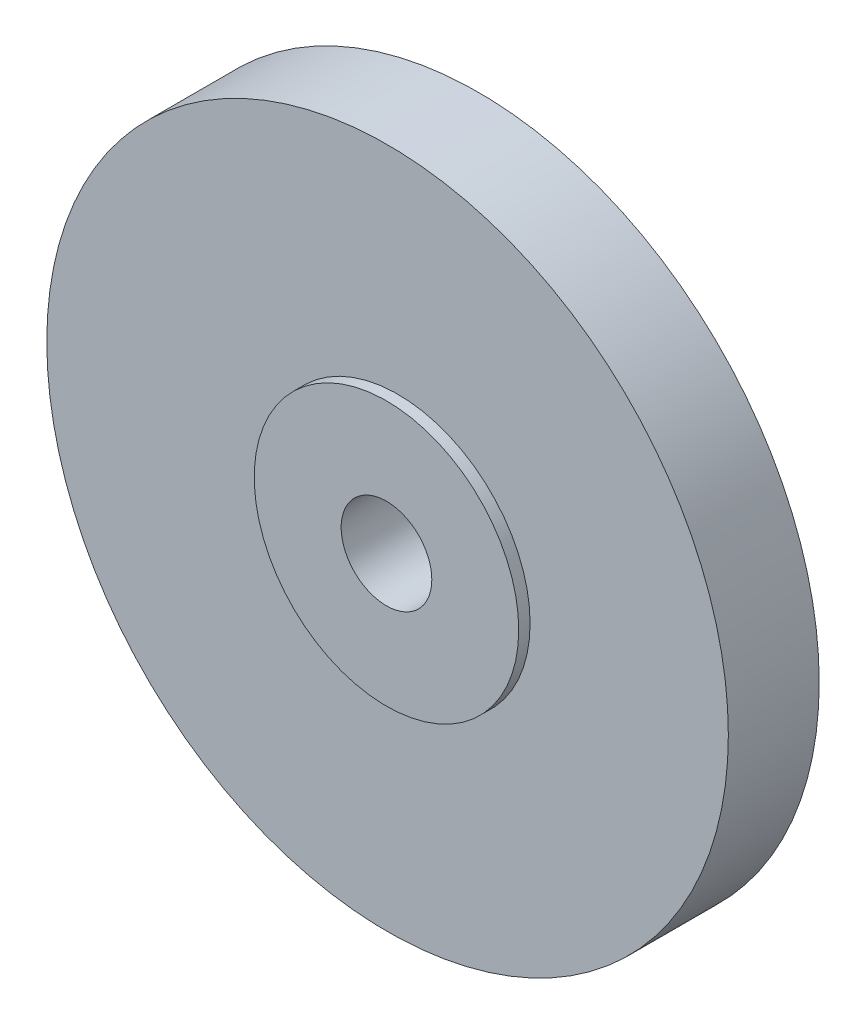
SolidWorks part; units mm, degrees
ref_plane "Alzado" through (0, 0, 0) normal (0, 0, 1) x (1, 0, 0)
ref_plane "Planta" through (0, 0, 0) normal (0, 1, 0) x (1, 0, 0)
ref_plane "Vista lateral" through (0, 0, 0) normal (1, 0, 0) x (0, 0, -1)
sketch "Croquis1" plane through (0, 0, 0) normal (0, 0, 1) x (1, 0, 0)
  circle A0 centre (-9.0502, 2.1195) radius 300
  dimension "D1" = 600
extrude "Saliente-Extruir1" add sketch "Croquis1" along normal blind 80
sketch "Croquis2" plane through (0, 0, 80) normal (0, 0, 1) x (1, 0, 0)
  circle A0 centre (0, 0) radius 116.4272
extrude "Saliente-Extruir2" add sketch "Croquis2" along normal blind 10
sketch "Croquis3" plane through (0, 0, 90) normal (0, 0, 1) x (1, 0, 0)
  circle A0 centre (0, 0) radius 39.9003
extrude "Cortar-Extruir1" cut sketch "Croquis3" against normal blind 90
